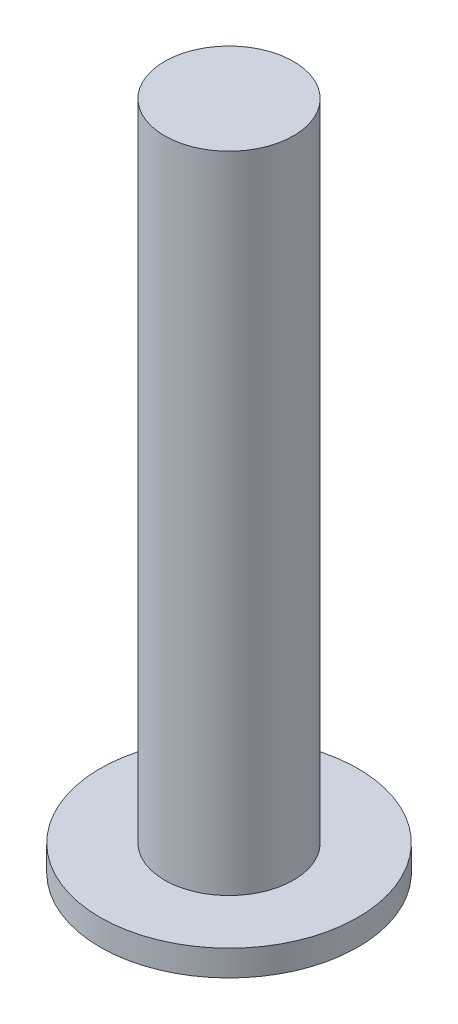
SolidWorks part; units mm, degrees
ref_plane "Front Plane" through (0, 0, 0) normal (0, 0, 1) x (1, 0, 0)
ref_plane "Top Plane" through (0, 0, 0) normal (0, 1, 0) x (1, 0, 0)
ref_plane "Right Plane" through (0, 0, 0) normal (1, 0, 0) x (0, 0, -1)
sketch "Sketch1" plane through (0, 0, 0) normal (0, 1, 0) x (1, 0, 0)
  circle A0 centre (0, 0) radius 100
extrude "Boss-Extrude1" add sketch "Sketch1" along normal blind 20 contours A0
sketch "Sketch2" plane through (0, 20, 0) normal (0, 1, 0) x (1, 0, 0)
  circle A0 centre (0, 0) radius 50
extrude "Boss-Extrude2" add sketch "Sketch2" along normal blind 500
